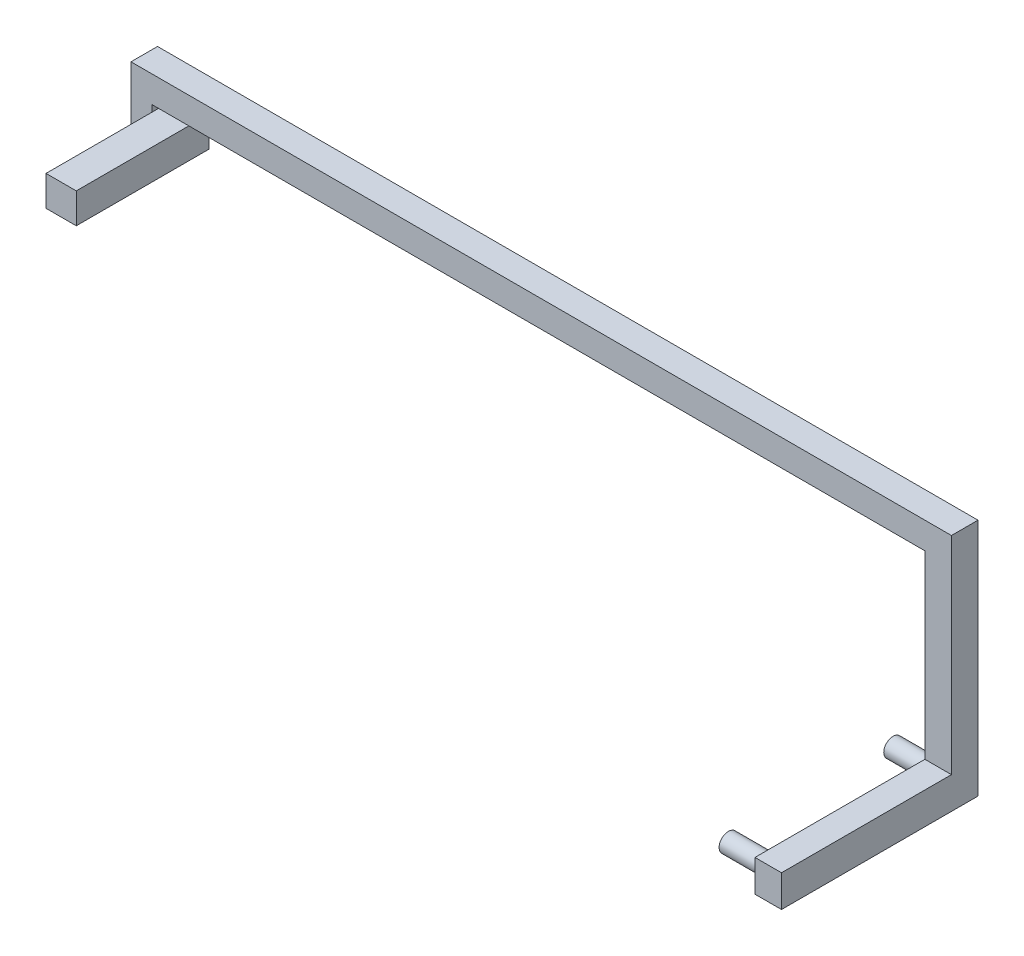
SolidWorks part; units mm, degrees
ref_plane "Front Plane" through (0, 0, 0) normal (0, 0, 1) x (1, 0, 0)
ref_plane "Top Plane" through (0, 0, 0) normal (0, 1, 0) x (1, 0, 0)
ref_plane "Right Plane" through (0, 0, 0) normal (1, 0, 0) x (0, 0, -1)
sketch "Sketch1" plane through (0, 0, 0) normal (0, 0, 1) x (1, 0, 0)
  line L0 (0, 5.7) -> (0, 6.9)
  line L1 (0, 0) -> (5.7, 0)
  line L3 (0, 5.7) -> (5.7, 5.7)
  line L4 (5.7, 0) -> (5.7, 5.7)
  line L5 (0, 0) -> (-4, 0)
  line L6 (-4, 0) -> (-4, 11.9)
  line L7 (-4, 11.9) -> (5.5, 11.9)
  line L8 (0, 6.9) -> (5.5, 6.9)
  line L10 (5.5, 11.9) -> (150.5, 11.9)
  line L11 (5.5, 6.9) -> (145.5, 6.9)
  line L12 (150.5, 6.9) -> (150.5, 11.9)
  line L13 (150.5, 6.9) -> (150.5, -33.1)
  line L14 (145.5, 6.9) -> (145.5, -33.1)
  line L15 (145.5, -33.1) -> (150.5, -33.1)
  dimension "D1" = 5.7
  dimension "D2" = 5.7
  dimension "D3" = 1.2
  dimension "D4" = 4
  dimension "D5" = 11.9
  dimension "D6" = 9.5
  dimension "D7" = 5.5
  dimension "D8" = 5
  dimension "D9" = 145
  dimension "D10" = 145
  dimension "D11" = 5
  dimension "D12" = 45
  dimension "D14" = 5
  dimension "D15" = 5
extrude "Boss-Extrude1" add sketch "Sketch1" along normal blind 5
sketch "Sketch2" plane through (0, 0, 5) normal (0, 0, 1) x (1, 0, 0)
  line L1 (5.7, 5.7) -> (0, 5.7)
  line L2 (5.7, 5.7) -> (5.7, 0)
  line L3 (5.7, 0) -> (0, 0)
  line L4 (0, 5.7) -> (0, 0)
extrude "Boss-Extrude2" add sketch "Sketch2" along normal blind 20 contours L2 L1 L4 L3
sketch "Sketch3" plane through (0, 0, 5) normal (0, 0, 1) x (1, 0, 0)
  line L0 (150.5, -33.1) -> (150.5, 11.9) construction
  line L1 (145.5, -33.1) -> (150.5, -33.1)
  line L2 (145.5, -33.1) -> (145.5, -27.1)
  line L3 (145.5, -27.1) -> (150.5, -27.1)
  line L4 (150.5, -33.1) -> (150.5, -27.1)
  dimension "D1" = 6
extrude "Boss-Extrude3" add sketch "Sketch3" along normal blind 32
sketch "Sketch4" plane through (145.5, 0, 0) normal (-1, 0, 0) x (0, 0, 1)
  line L1 (0, 6.9) -> (0, -33.1) construction
  line L3 (37, -27.1) -> (5, -27.1) construction
  circle A0 centre (3, -30.1) radius 1.75
  circle A1 centre (34, -30.1) radius 1.75
  dimension "D1" = 31
  dimension "D3" = 3.5
  dimension "D4" = 3.5
  dimension "D2" = 3
  dimension "D5" = 3
  dimension "D6" = 3
extrude "Boss-Extrude4" add sketch "Sketch4" along normal blind 8
